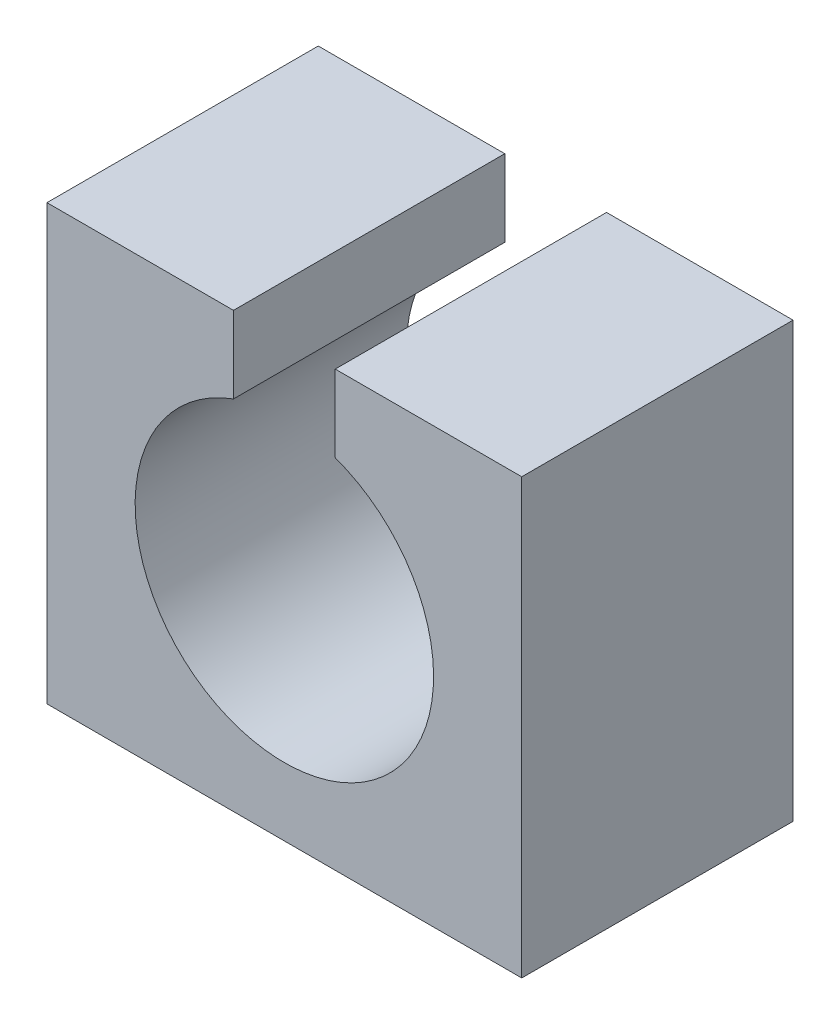
SolidWorks part; units mm, degrees
material "1060-H18"
ref_plane "前视基准面" through (0, 0, 0) normal (0, 0, 1) x (1, 0, 0)
ref_plane "上视基准面" through (0, 0, 0) normal (0, 1, 0) x (1, 0, 0)
ref_plane "右视基准面" through (0, 0, 0) normal (1, 0, 0) x (0, 0, -1)
sketch "草图1" plane through (0, 0, 0) normal (0, 0, 1) x (1, 0, 0)
  line L1 (-35, -32) -> (35, -32)
  line L2 (-35, -32) -> (-35, 32)
  line L3 (-35, 32) -> (35, 32)
  line L4 (35, -32) -> (35, 32)
  line L5 (-35, -32) -> (35, 32) construction
  line L6 (-35, 32) -> (35, -32) construction
  point P0 (0, 0)
  dimension "D1" = 70
  dimension "D2" = 64
extrude "凸台-拉伸1" add sketch "草图1" along normal mid plane 40
sketch "草图2" plane through (0, 0, 20) normal (0, 0, 1) x (1, 0, 0)
  circle A0 centre (0, 0) radius 22
  dimension "D1" = 44
extrude "切除-拉伸1" cut sketch "草图2" against normal blind 40
sketch "草图3" plane through (0, 32, 0) normal (0, 1, 0) x (1, 0, 0)
  line L0 (35, 20) -> (-35, 20) construction
  line L1 (-7.5, -20) -> (7.5, -20)
  line L2 (-7.5, -20) -> (-7.5, 20)
  line L3 (-7.5, 20) -> (7.5, 20)
  line L4 (7.5, -20) -> (7.5, 20)
  line L5 (-7.5, -20) -> (7.5, 20) construction
  line L6 (-7.5, 20) -> (7.5, -20) construction
  point P0 (0, 0)
  dimension "D1" = 15
extrude "切除-拉伸2" cut sketch "草图3" against normal blind 20
